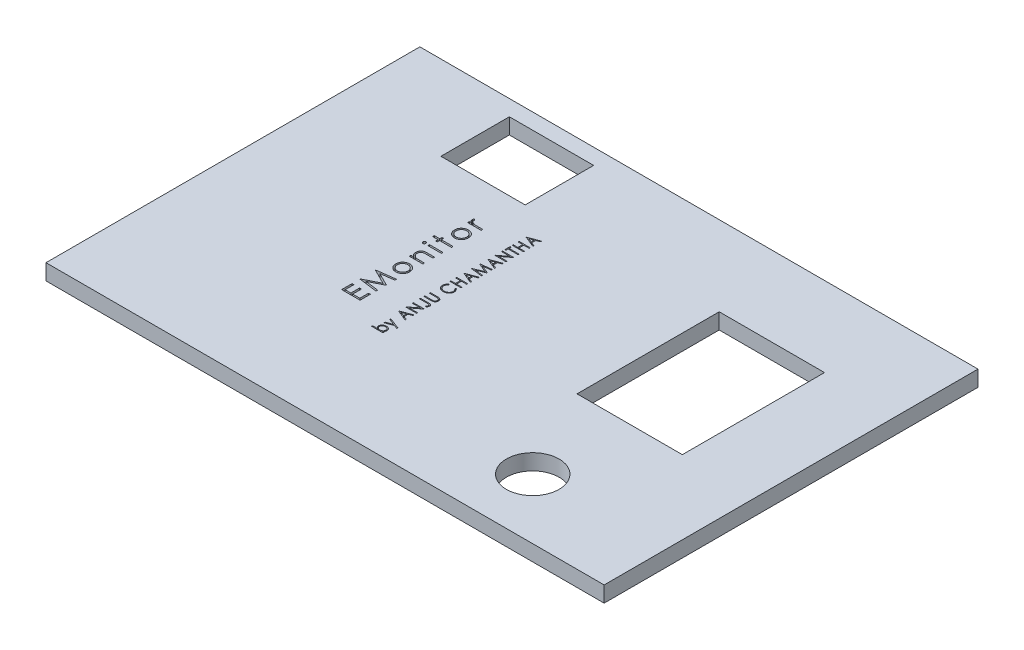
SolidWorks part; units mm, degrees
ref_plane "Front Plane" through (0, 0, 0) normal (0, 0, 1) x (1, 0, 0)
ref_plane "Top Plane" through (0, 0, 0) normal (0, 1, 0) x (1, 0, 0)
ref_plane "Right Plane" through (0, 0, 0) normal (1, 0, 0) x (0, 0, -1)
sketch "Sketch1" plane through (0, 0, 0) normal (0, 1, 0) x (1, 0, 0)
  line L1 (-95.7931, 35.6585) -> (10.2069, 35.6585)
  line L2 (-95.7931, 35.6585) -> (-95.7931, -35.3415)
  line L3 (-95.7931, -35.3415) -> (10.2069, -35.3415)
  line L4 (10.2069, 35.6585) -> (10.2069, -35.3415)
  line L5 (-23.7931, -6.4895) -> (-3.7931, -6.4895)
  line L6 (-23.7931, -6.4895) -> (-23.7931, 20.5105)
  line L7 (-23.7931, 20.5105) -> (-3.7931, 20.5105)
  line L8 (-3.7931, -6.4895) -> (-3.7931, 20.5105)
  circle A0 centre (-14.7931, -23.9046) radius 5
  dimension "D4" = 10
  dimension "D1" = 71
  dimension "D2" = 106
  dimension "D3" = 81
  dimension "D5" = 20
  dimension "D6" = 27
  dimension "D7" = 72
extrude "Boss-Extrude3" add sketch "Sketch1" along normal blind 3 contours L2 L1 L4 L3 | L6 L5 L8 L7 | A0
sketch "Sketch2" plane through (0, 3, 0) normal (0, 1, 0) x (1, 0, 0)
  line L0 (-95.7931, 35.6585) -> (10.2069, 35.6585) construction
  line L1 (-75.7931, 32.6585) -> (-59.7931, 32.6585)
  line L2 (-75.7931, 32.6585) -> (-75.7931, 19.6585)
  line L3 (-75.7931, 19.6585) -> (-59.7931, 19.6585)
  line L4 (-59.7931, 32.6585) -> (-59.7931, 19.6585)
  line L5 (-95.7931, 35.6585) -> (-95.7931, -35.3415) construction
  dimension "D1" = 13
  dimension "D2" = 16
  dimension "D3" = 3
  dimension "D4" = 20
extrude "Cut-Extrude1" cut sketch "Sketch2" against normal through all contours L2 L1 L4 L3
sketch "Sketch3" plane through (0, 3, 0) normal (0, 1, 0) x (1, 0, 0)
  line L0 (-52.2566, 35.6585) -> (-52.2566, -35.3415) construction
  line L2 (-95.7931, -35.3415) -> (10.2069, -35.3415) construction
  line L3 (-59.7931, -35.3415) -> (-59.7931, 35.6585) construction
  line L4 (-95.7931, 35.6585) -> (10.2069, 35.6585) construction
  text T0 "EMonitor" font "Century Gothic" height 3.5
  text T1 "by ANJU CHAMANTHA" font "Century Gothic" height in points 8
extrude "Cut-Extrude2" cut sketch "Sketch3" against normal blind 1
